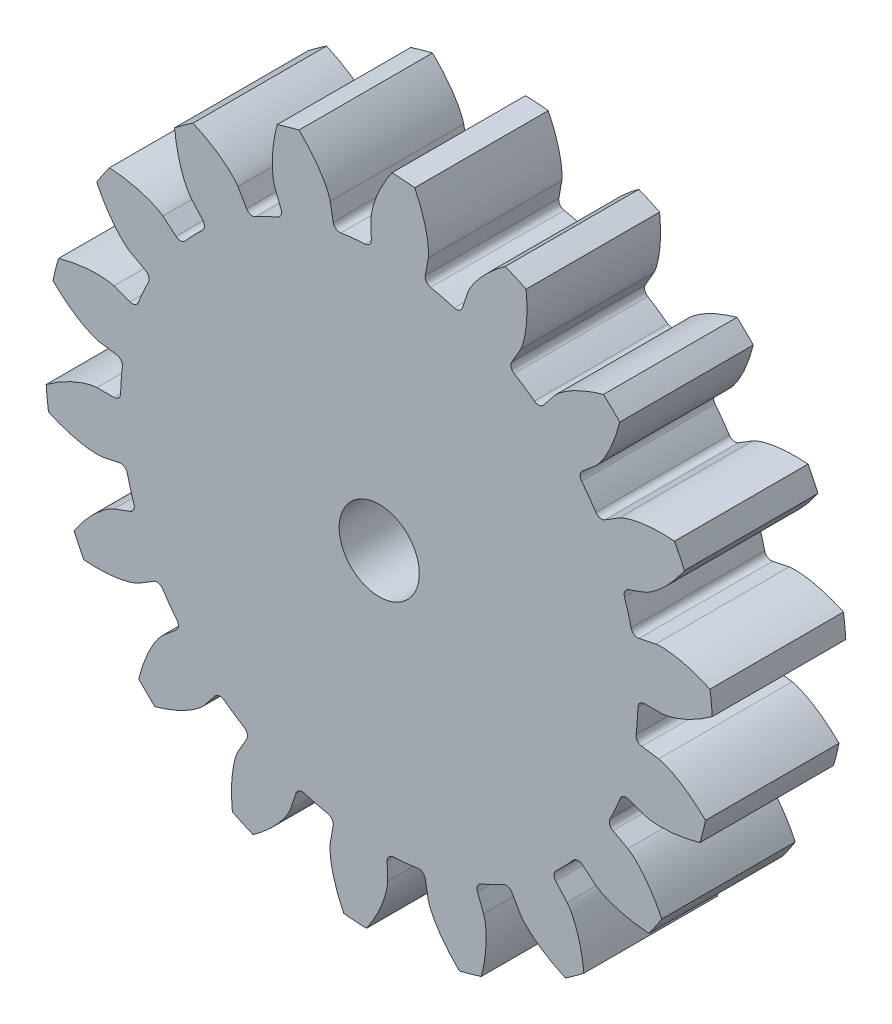
SolidWorks part; units mm, degrees
ref_plane "Front Plane" through (0, 0, 0) normal (0, 0, 1) x (1, 0, 0)
ref_plane "Top Plane" through (0, 0, 0) normal (0, 1, 0) x (1, 0, 0)
ref_plane "Right Plane" through (0, 0, 0) normal (1, 0, 0) x (0, 0, -1)
sketch "Sketch1" plane through (0, 0, 0) normal (0, 0, 1) x (1, 0, 0)
  circle A0 centre (0, 0) radius 25
  dimension "D1" = 50
extrude "Boss-Extrude1" add sketch "Sketch1" along normal blind 10
sketch "Sketch2" plane through (0, 0, 10) normal (0, 0, 1) x (1, 0, 0)
  line L0 (19.8687, 0) -> (21.1431, 0)
  line L1 (0, 0) -> (-24.9346, 1.8075) construction
  line L2 (19.661, -2.8655) -> (20.922, -3.0492)
  circle A0 centre (0, 0) radius 22.5 construction
  circle A1 centre (0, 0) radius 21.1431 construction
  arc A2 (19.2367, -2.311) -> (19.3689, -0.4874) centre (0, 0) ccw
  circle A3 centre (0, 0) radius 25 construction
  arc A4 (19.661, -2.8655) -> (19.2367, -2.311) centre (19.7331, -2.3707) cw
  arc A5 (19.3689, -0.4874) -> (19.8687, 0) centre (19.8687, -0.5) cw
  spline S0 degree 4 poles (21.1431, 0) (21.1503, 0.0001) (21.1706, 0.0007) (21.2089, 0.0031) (21.2713, 0.0089) (21.3506, 0.0189) (21.4529, 0.0349) (21.5731, 0.0576) (21.7047, 0.0866) (21.8472, 0.1226) (21.9889, 0.1624) (22.1296, 0.2056) (22.2692, 0.2519) (22.4376, 0.3118) (22.6384, 0.3889) (22.8714, 0.4866) (23.1335, 0.6064) (23.3982, 0.738) (23.6564, 0.8752) (23.9146, 1.0228) (24.1626, 1.1719) (24.4171, 1.3356) (24.6505, 1.4914) (24.9084, 1.6756) (25.1156, 1.8272) (25.3848, 2.0374) (25.5426, 2.1647) (25.7259, 2.3171) (25.8065, 2.3866) (25.8561, 2.4294) knots 0 0 0 0 0 0.005377 0.015084 0.028532 0.04661 0.064855 0.092111 0.119476 0.146842 0.174209 0.201575 0.228941 0.256307 0.307035 0.361767 0.4165 0.471232 0.525964 0.580697 0.635429 0.690161 0.744894 0.799626 0.854358 0.909091 0.954545 1 1 1 1 1 construction
  spline S1 degree 4 poles (21.1431, 0) (21.1503, 0.0001) (21.1706, 0.0007) (21.2089, 0.0031) (21.2713, 0.0089) (21.3506, 0.0189) (21.4529, 0.0349) (21.5731, 0.0576) (21.7047, 0.0866) (21.8472, 0.1226) (21.9889, 0.1624) (22.1296, 0.2056) (22.2692, 0.2519) (22.4376, 0.3118) (22.6384, 0.3889) (22.8714, 0.4866) (23.1335, 0.6064) (23.3982, 0.738) (23.6564, 0.8752) (23.9146, 1.0228) (24.1626, 1.1719) (24.4171, 1.3356) (24.6505, 1.4914) (24.9084, 1.6756) (25.1156, 1.8272) (25.3265, 1.9919) (25.4286, 2.0732) (25.4806, 2.1152) knots 0 0 0 0 0 0.005377 0.015084 0.028532 0.04661 0.064855 0.092111 0.119476 0.146842 0.174209 0.201575 0.228941 0.256307 0.307035 0.361767 0.4165 0.471232 0.525964 0.580697 0.635429 0.690161 0.744894 0.799626 0.854358 0.909091 0.909091 0.909091 0.909091 0.909091
  spline S2 degree 4 poles (20.922, -3.0492) (20.9292, -3.0504) (20.9492, -3.0539) (20.9867, -3.0618) (21.0476, -3.0766) (21.1247, -3.0979) (21.2236, -3.1285) (21.3392, -3.1683) (21.4653, -3.216) (21.6012, -3.2721) (21.7356, -3.3319) (21.8686, -3.395) (22.0001, -3.4609) (22.1581, -3.5445) (22.3457, -3.6497) (22.5622, -3.78) (22.8043, -3.9363) (23.0471, -4.1047) (23.2829, -4.2778) (23.5171, -4.4611) (23.7409, -4.6443) (23.9692, -4.8431) (24.1777, -5.0309) (24.4064, -5.2504) (24.5895, -5.4303) (24.8256, -5.6771) (24.9634, -5.8258) (25.1227, -6.003) (25.1925, -6.0835) (25.2354, -6.1329) knots 0 0 0 0 0 0.005377 0.015084 0.028532 0.04661 0.064855 0.092111 0.119476 0.146842 0.174209 0.201575 0.228941 0.256307 0.307035 0.361767 0.4165 0.471232 0.525964 0.580697 0.635429 0.690161 0.744894 0.799626 0.854358 0.909091 0.954545 1 1 1 1 1 construction
  spline S3 degree 4 poles (20.922, -3.0492) (20.9292, -3.0504) (20.9492, -3.0539) (20.9867, -3.0618) (21.0476, -3.0766) (21.1247, -3.0979) (21.2236, -3.1285) (21.3392, -3.1683) (21.4653, -3.216) (21.6012, -3.2721) (21.7356, -3.3319) (21.8686, -3.395) (22.0001, -3.4609) (22.1581, -3.5445) (22.3457, -3.6497) (22.5622, -3.78) (22.8043, -3.9363) (23.0471, -4.1047) (23.2829, -4.2778) (23.5171, -4.4611) (23.7409, -4.6443) (23.9692, -4.8431) (24.1777, -5.0309) (24.4064, -5.2504) (24.5895, -5.4303) (24.7744, -5.6236) (24.8638, -5.7188) (24.9092, -5.7679) knots 0 0 0 0 0 0.005377 0.015084 0.028532 0.04661 0.064855 0.092111 0.119476 0.146842 0.174209 0.201575 0.228941 0.256307 0.307035 0.361767 0.4165 0.471232 0.525964 0.580697 0.635429 0.690161 0.744894 0.799626 0.854358 0.909091 0.909091 0.909091 0.909091 0.909091
  dimension "D1" = 45
  dimension "D2" = 42.2862
  dimension "D3" = 38.75
  dimension "D6" = 0.5
  dimension "D4" = 4.146
  dimension "D5" = 4.146
extrude "Cut-Extrude1" cut sketch "Sketch2" against normal through all and the other way through all
ref_axis "Axis2" through (0, 0, 10) along (0, 0, -1)
pattern_circular "CirPattern6" count 18 over 360 about axis through (0, 0, 10) along (0, 0, -1) of "Cut-Extrude1"
sketch "Sketch3" plane through (0, 0, 10) normal (0, 0, 1) x (1, 0, 0)
  circle A0 centre (0, 0) radius 3
  dimension "D1" = 6
extrude "Cut-Extrude2" cut sketch "Sketch3" against normal blind 10
equation "\"m\"= 2.5'module"
equation "\"p\"= 1 / \"m\"'Diametral pitch"
equation "\"N\"= 18'Number of teeth"
equation "\"phi\"= 20'pressure angle"
equation "\"a\"= \"m\"'addendum"
equation "\"b\"= 1.25 * \"m\"'deddendum"
equation "\"c\"= \"b\" - \"a\"'clearance"
equation "\"dp\"= \"N\" * \"m\"'pitch circle diameter"
equation "\"db\"= \"dp\" * cos ( \"phi\" )'base circle diameter"
equation "\"D1@Sketch1\" = \"dp\" + 2 * \"a\"'Addendum circle dia "
equation "\"D1@Sketch2\" = \"dp\"'pitch circle dia "
equation "\"D2@Sketch2\"= \"db\" 'base circle dia"
equation "\"D3@Sketch2\"= \"dp\" - 2 * \"b\" 'deddendum circle dia"
equation "\"alpha\"= sqr ( \"dp\" ^ 2 - \"db\" ^ 2 ) / \"db\" * 180 / pi - \"phi\""
equation "\"D4@Sketch2\" = 360 / ( 4 * \"N\" ) - \"alpha\""
equation "\"D5@Sketch2\" = \"D4@Sketch2\""
equation "\"D6@Sketch2\" = 0.8 * \"c\""
